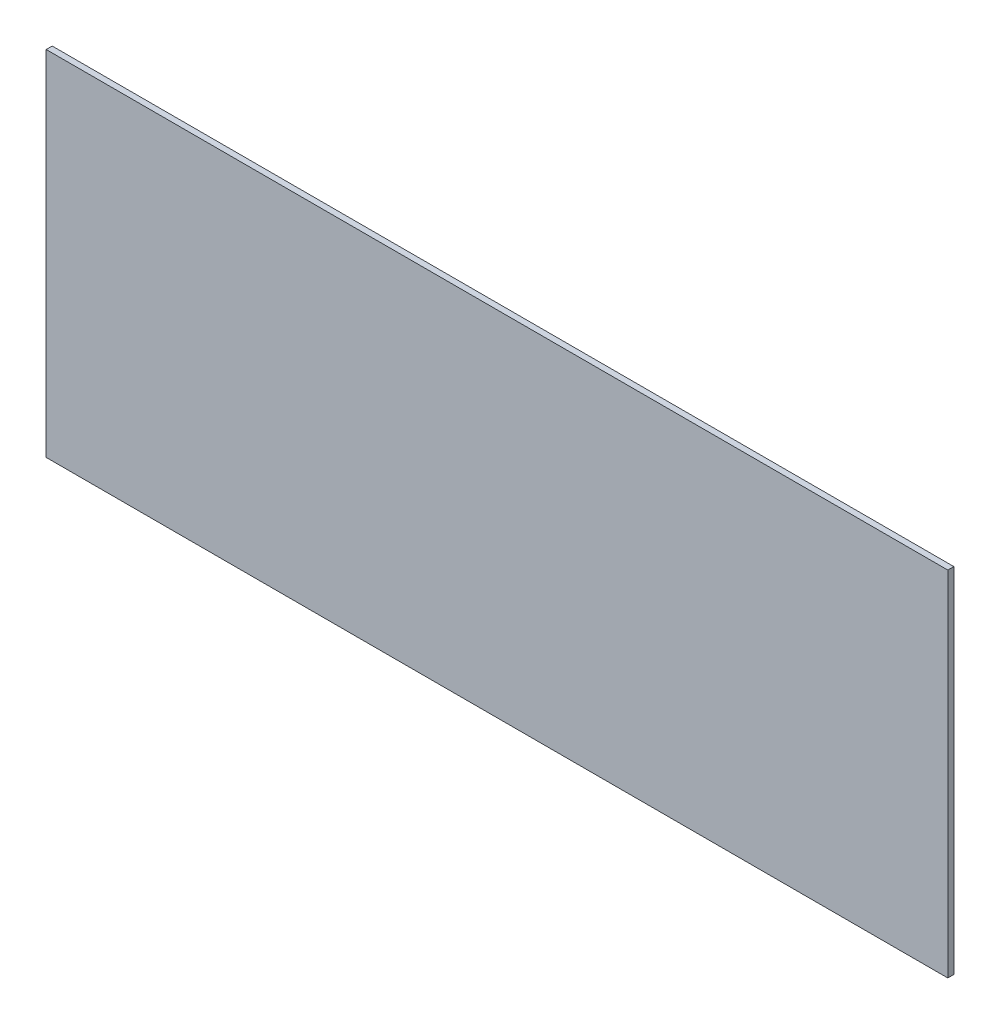
SolidWorks part; units mm, degrees
ref_plane "Plan de face" through (0, 0, 0) normal (0, 0, 1) x (1, 0, 0)
ref_plane "Plan de dessus" through (0, 0, 0) normal (0, 1, 0) x (1, 0, 0)
ref_plane "Plan de droite" through (0, 0, 0) normal (1, 0, 0) x (0, 0, -1)
sketch "Esquisse1" plane through (0, 0, 0) normal (0, 0, 1) x (1, 0, 0)
  line L1 (-373.5, -146.35) -> (373.5, -146.35)
  line L2 (-373.5, -146.35) -> (-373.5, 146.35)
  line L3 (-373.5, 146.35) -> (373.5, 146.35)
  line L4 (373.5, -146.35) -> (373.5, 146.35)
  line L5 (-373.5, -146.35) -> (373.5, 146.35) construction
  line L6 (-373.5, 146.35) -> (373.5, -146.35) construction
  point P0 (0, 0)
  dimension "D1" = 747
  dimension "D2" = 292.7
extrude "Boss.-Extru.1" add sketch "Esquisse1" along normal blind 5
